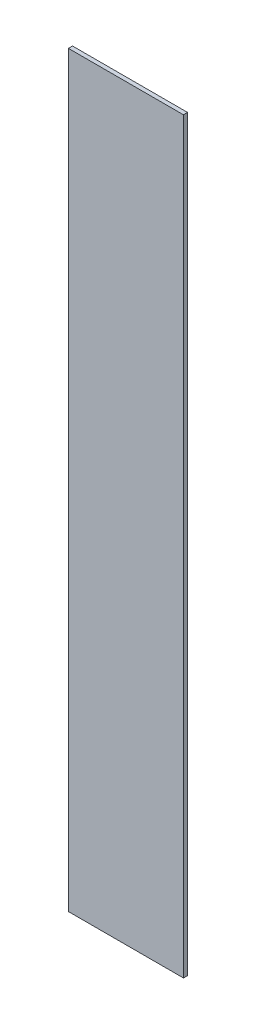
SolidWorks part; units mm, degrees
ref_plane "Front Plane" through (0, 0, 0) normal (0, 0, 1) x (1, 0, 0)
ref_plane "Top Plane" through (0, 0, 0) normal (0, 1, 0) x (1, 0, 0)
ref_plane "Right Plane" through (0, 0, 0) normal (1, 0, 0) x (0, 0, -1)
other "Configuration Table"
sketch "Sketch1" plane through (0, 0, 0) normal (0, 0, 1) x (1, 0, 0)
  line L1 (623, 119) -> (651, 119)
  line L2 (623, 119) -> (623, 301)
  line L3 (623, 301) -> (651, 301)
  line L4 (651, 119) -> (651, 301)
extrude "PACK_pano_kapagi_kulp_cukuru_1" add sketch "Sketch1" along normal blind 1 from offset 26 separate body
